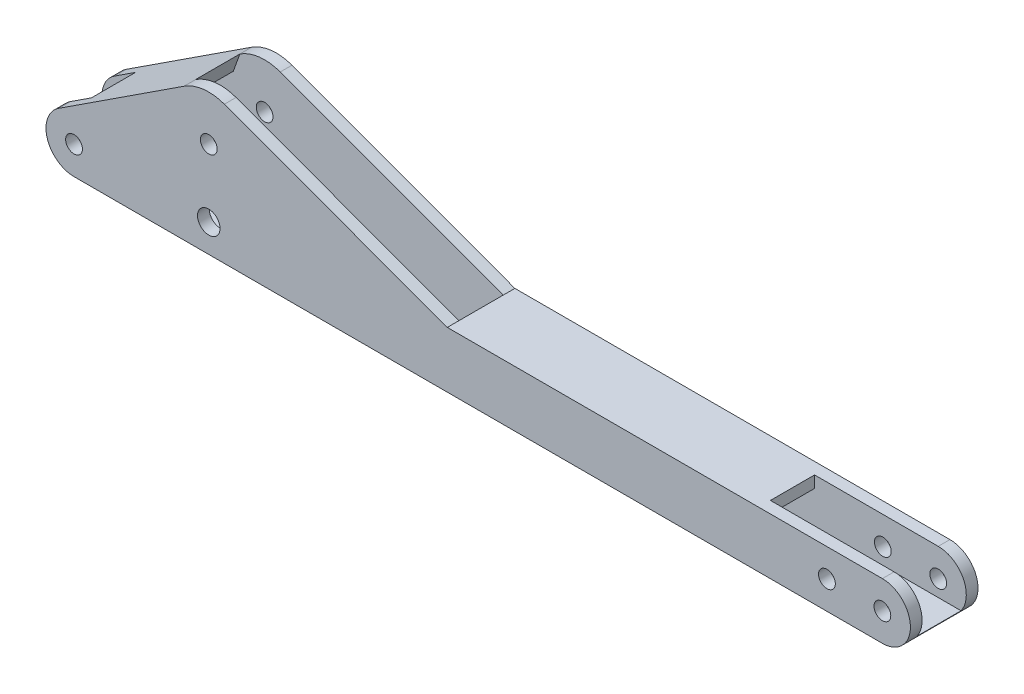
SolidWorks part; units mm, degrees
ref_plane "Front Plane" through (0, 0, 0) normal (0, 0, 1) x (1, 0, 0)
ref_plane "Top Plane" through (0, 0, 0) normal (0, 1, 0) x (1, 0, 0)
ref_plane "Right Plane" through (0, 0, 0) normal (1, 0, 0) x (0, 0, -1)
sketch "Sketch1" plane through (0, 0, 0) normal (0, 0, 1) x (1, 0, 0)
  line L0 (0, 0) -> (3660, 0) construction
  line L1 (610, 305) -> (610, 0) construction
  line L2 (-69.4149, 106.3512) -> (497.9523, 476.6692)
  line L3 (0, -127) -> (3660, -127)
  line L4 (3660, 127) -> (1690, 127)
  line L5 (1690, 127) -> (680.6304, 497.4483)
  circle A0 centre (0, 0) radius 38
  arc A1 (-69.4149, 106.3512) -> (0, -127) centre (0, 0) ccw
  circle A2 centre (610, 0) radius 51
  circle A3 centre (610, 305) radius 38
  circle A4 centre (3409, 0) radius 38
  circle A5 centre (3660, 0) radius 38
  arc A6 (680.6304, 497.4483) -> (497.9523, 476.6692) centre (610, 305) ccw
  arc A7 (3660, -127) -> (3660, 127) centre (3660, 0) ccw
  point P3 (3579.9306, -127)
  point P12 (823.474, 124.7938)
  point P17 (0, 0)
  point P20 (610, 93.8493)
  point P22 (3413.5094, 47.3644)
  dimension "D1" = 76
  dimension "D3" = 127
  dimension "D6" = 205
  dimension "D8" = 76
  dimension "D9" = 102
  dimension "D10" = 76
  dimension "D11" = 76
  dimension "D2" = 610
  dimension "D4" = 3050
  dimension "D5" = 305
  dimension "D7" = 1970
  dimension "D12" = 251
extrude "Boss-Extrude1" add sketch "Sketch1" along normal mid plane 306
sketch "Sketch2" plane through (0, 0, 0) normal (0, 0, 1) x (1, 0, 0)
  line L0 (3660, 0) -> (3660, 254.8834) construction
  line L1 (3660, 127) -> (1690, 127) construction
  line L6 (0, 0) -> (0, 329.255) construction
  line L7 (54.4684, 123.9189) -> (25.5, 168.3017)
  line L8 (54.4684, 123.9189) -> (468.1048, 393.8975)
  line L9 (3100, 127) -> (3100, 74)
  line L10 (3100, 74) -> (1670.5485, 74)
  line L11 (1670.5485, 74) -> (1690, 127)
  line L12 (299.4438, -74) -> (3763.2134, -74)
  line L13 (299.4438, -74) -> (218.2421, -127)
  line L14 (54.4684, 123.9189) -> (218.2421, -127) construction
  line L15 (1690, 127) -> (680.6304, 497.4483) construction
  line L16 (468.1048, 393.8975) -> (497.9523, 476.6692)
  line L17 (25.5, 168.3017) -> (25.5, 441.7042)
  line L18 (25.5, 441.7042) -> (-335.5787, 441.7042)
  line L19 (-335.5787, 441.7042) -> (-335.5787, -282.7336)
  line L20 (-335.5787, -282.7336) -> (218.2421, -282.7336)
  line L21 (218.2421, -282.7336) -> (218.2421, -127)
  line L22 (497.9523, 476.6692) -> (497.9523, 728.3337)
  line L23 (497.9523, 728.3337) -> (1690, 728.3337)
  line L24 (1690, 728.3337) -> (1690, 127)
  line L25 (3100, 127) -> (3100, 728.3337)
  line L26 (3100, 728.3337) -> (4168.7733, 728.3337)
  line L27 (4168.7733, 728.3337) -> (4168.7733, -74)
  line L28 (4168.7733, -74) -> (3763.2134, -74)
  line L29 (0, -127) -> (3660, -127) construction
  line L30 (497.9523, 476.6692) -> (-69.4149, 106.3512) construction
  dimension "D1" = 25.5
  dimension "D2" = 53
  dimension "D3" = 53
  dimension "D4" = 1410
  dimension "D5" = 53
  dimension "D6" = 1970
extrude "Cut-Extrude1" cut sketch "Sketch2" against normal mid plane 200
